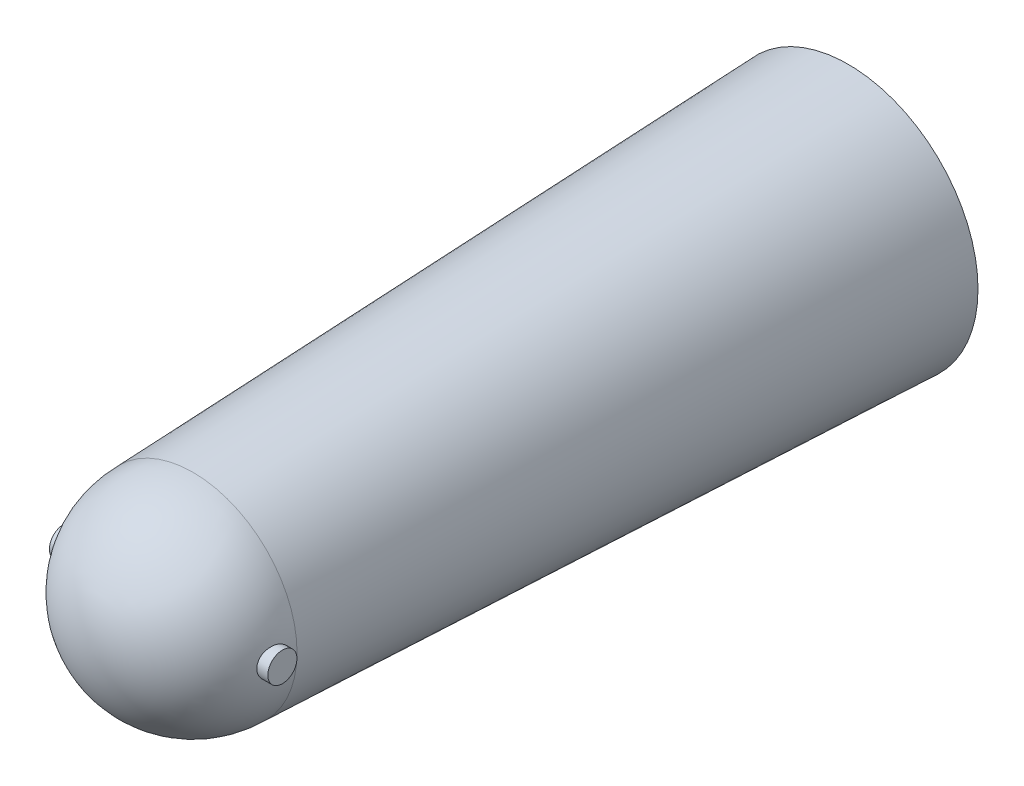
SolidWorks part; units mm, degrees
ref_plane "Front Plane" through (0, 0, 0) normal (0, 0, 1) x (1, 0, 0)
ref_plane "Top Plane" through (0, 0, 0) normal (0, 1, 0) x (1, 0, 0)
ref_plane "Right Plane" through (0, 0, 0) normal (1, 0, 0) x (0, 0, -1)
sketch "Sketch1" plane through (0, 0, 0) normal (0, 0, 1) x (1, 0, 0)
  circle A0 centre (0, 0) radius 89.125
  dimension "D1" = 178.25
extrude "Boss-Extrude1" add sketch "Sketch1" along normal blind 450 draft 2.25
sketch "Sketch2" plane through (0, 0, 450) normal (0, 0, 1) x (1, 0, 0)
  line L0 (0, 71.4445) -> (0, -71.4445)
  arc A0 (0, 71.4445) -> (0, -71.4445) centre (0, 0) ccw
  circle A1 centre (0, 0) radius 71.4445 construction
revolve "Revolve1" add sketch "Sketch2" angle 360 about L0
sketch "Sketch3" plane through (0, 0, 0) normal (0, 0, -1) x (-1, 0, 0)
  line L0 (-79, 0) -> (79, 0)
  arc A0 (-79, 0) -> (79, 0) centre (0, 0) ccw
  dimension "D1" = 79
revolve "Cut-Revolve1" cut sketch "Sketch3" angle 360 about L0
ref_plane "Plane1" through (65, 0, 0) normal (1, 0, 0) x (0, 0, -1)
sketch "Sketch4" plane through (65, 0, 0) normal (1, 0, 0) x (0, 0, -1)
  circle A0 centre (-463.6227, 0) radius 10
  dimension "D1" = 20
ref_plane "Plane2" through (-65, 0, 0) normal (1, 0, 0) x (0, 0, -1)
sketch "Sketch5" plane through (-65, 0, 0) normal (1, 0, 0) x (0, 0, -1)
  circle A0 centre (-463.6227, 0) radius 10 construction
  circle A1 centre (-463.6227, 0) radius 10
extrude "Boss-Extrude3" add sketch "Sketch5" against normal blind 10 separate body
extrude "Boss-Extrude4" add sketch "Sketch4" along normal blind 10 separate body
sketch "Sketch6" plane through (65, 0, 0) normal (1, 0, 0) x (0, 0, -1)
  circle A0 centre (-25.5481, 0) radius 5
  dimension "D1" = 10
sketch "Sketch7" plane through (-65, 0, 0) normal (1, 0, 0) x (0, 0, -1)
  circle A0 centre (-25.5481, 0) radius 5 construction
  circle A1 centre (-25.5481, 0) radius 5
extrude "Cut-Extrude1" cut sketch "Sketch7" against normal blind 10
extrude "Cut-Extrude2" cut sketch "Sketch6" along normal blind 10 contours A0
